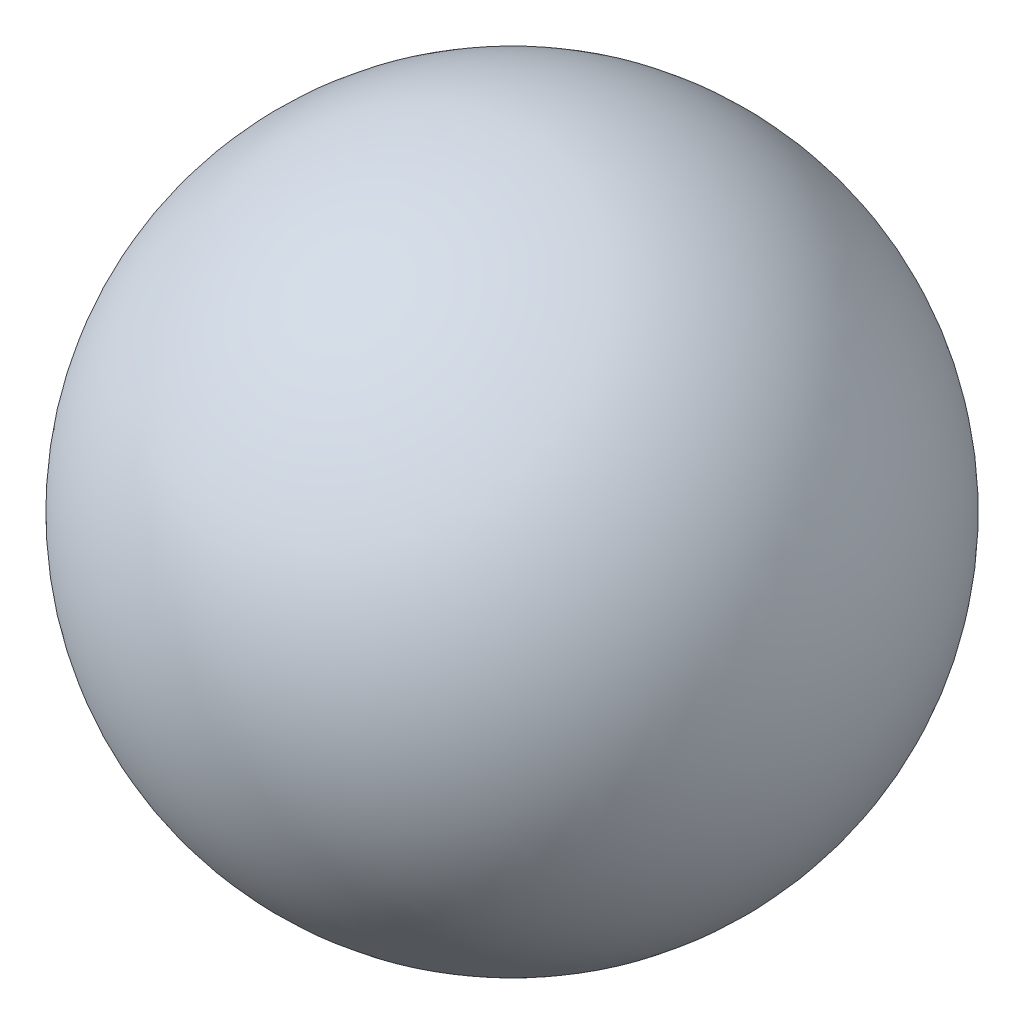
SolidWorks part; units mm, degrees
ref_plane "前视基准面" through (0, 0, 0) normal (0, 0, 1) x (1, 0, 0)
ref_plane "上视基准面" through (0, 0, 0) normal (0, 1, 0) x (1, 0, 0)
ref_plane "右视基准面" through (0, 0, 0) normal (1, 0, 0) x (0, 0, -1)
sketch "草图1" plane through (0, 0, 0) normal (0, 0, 1) x (1, 0, 0)
  line L0 (0, 21.5) -> (0, -21.5)
  arc A0 (0, 21.5) -> (0, -21.5) centre (0, 0) ccw
  dimension "D1" = 43
revolve "旋转3" add sketch "草图1" angle 360 about L0
sketch "草图3" plane through (0, 0, 0) normal (1, 0, 0) x (0, 0, -1)
  line L0 (-12.9, 17.2) -> (-12.9, -17.2)
  line L1 (-12.9, 0) -> (21.5, 0)
  circle A0 centre (0, 0) radius 21.5 construction
  circle A1 centre (0, 0) radius 21.5
  dimension "D1" = 34.4
